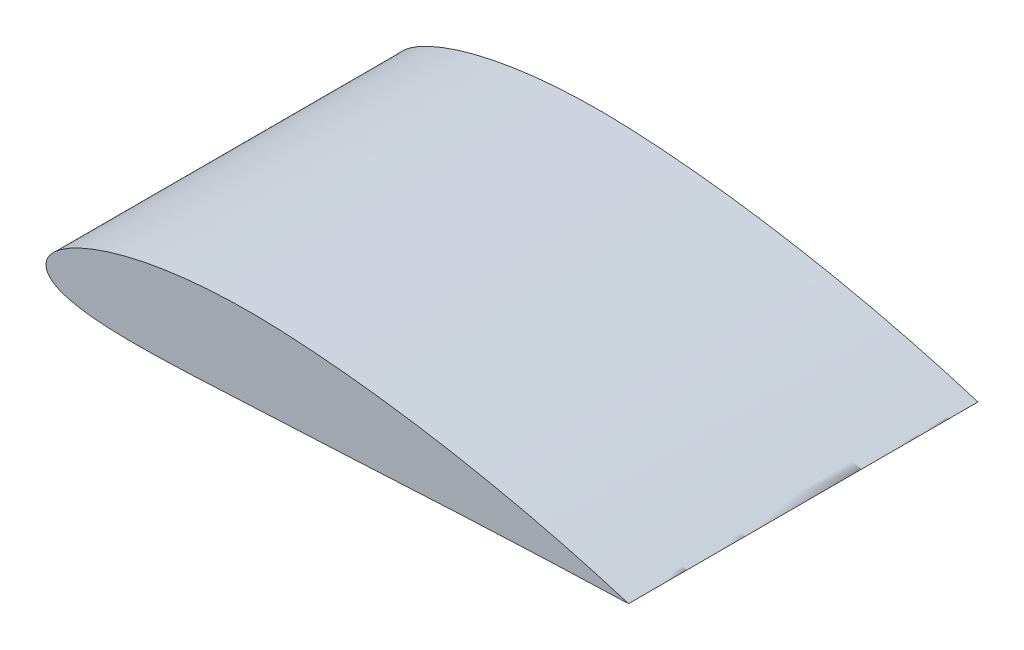
SolidWorks part; units mm, degrees
ref_plane "Front Plane" through (0, 0, 0) normal (1, 0, 0) x (0, 1, 0)
ref_plane "Top Plane" through (0, 0, 0) normal (0, 0, 1) x (0, 1, 0)
ref_plane "Right Plane" through (0, 0, 0) normal (0, 1, 0) x (-1, 0, 0)
curve "Curve1"
  spline degree 3 poles (0.9995, 0, 0) (1.0001, 0, 0) (0.9995, 0.0001, 0) (0.999, 0.0003, 0) (0.9976, 0.0007, 0) (0.996, 0.0012, 0) (0.9938, 0.0019, 0) (0.9912, 0.0027, 0) (0.9881, 0.0036, 0) (0.9845, 0.0047, 0) (0.9804, 0.0059, 0) (0.9759, 0.0073, 0) (0.9709, 0.0088, 0) (0.9655, 0.0104, 0) (0.9596, 0.0121, 0) (0.9532, 0.0139, 0) (0.9464, 0.0158, 0) (0.9392, 0.0179, 0) (0.9316, 0.02, 0) (0.9235, 0.0222, 0) (0.915, 0.0245, 0) (0.9061, 0.0269, 0) (0.8968, 0.0294, 0) (0.8871, 0.0319, 0) (0.877, 0.0345, 0) (0.8665, 0.0371, 0) (0.8557, 0.0397, 0) (0.8445, 0.0424, 0) (0.833, 0.0452, 0) (0.8212, 0.0479, 0) (0.809, 0.0507, 0) (0.7965, 0.0535, 0) (0.7837, 0.0563, 0) (0.7706, 0.059, 0) (0.7573, 0.0618, 0) (0.7436, 0.0645, 0) (0.7298, 0.0673, 0) (0.7157, 0.0699, 0) (0.7013, 0.0726, 0) (0.6868, 0.0752, 0) (0.6721, 0.0777, 0) (0.6571, 0.0802, 0) (0.6421, 0.0826, 0) (0.6268, 0.085, 0) (0.6115, 0.0873, 0) (0.596, 0.0895, 0) (0.5804, 0.0916, 0) (0.5647, 0.0936, 0) (0.5489, 0.0955, 0) (0.5331, 0.0973, 0) (0.5173, 0.099, 0) (0.5014, 0.1006, 0) (0.4855, 0.102, 0) (0.4696, 0.1034, 0) (0.4537, 0.1046, 0) (0.4379, 0.1057, 0) (0.4221, 0.1066, 0) (0.4064, 0.1074, 0) (0.3906, 0.1081, 0) (0.3749, 0.1085, 0) (0.3592, 0.1087, 0) (0.3437, 0.1087, 0) (0.3283, 0.1086, 0) (0.3131, 0.1081, 0) (0.298, 0.1075, 0) (0.2832, 0.1067, 0) (0.2687, 0.1057, 0) (0.2543, 0.1045, 0) (0.2402, 0.103, 0) (0.2264, 0.1014, 0) (0.2129, 0.0996, 0) (0.1997, 0.0977, 0) (0.1868, 0.0955, 0) (0.1743, 0.0932, 0) (0.1621, 0.0908, 0) (0.1502, 0.0882, 0) (0.1388, 0.0854, 0) (0.1277, 0.0826, 0) (0.117, 0.0796, 0) (0.1068, 0.0765, 0) (0.0969, 0.0733, 0) (0.0875, 0.07, 0) (0.0786, 0.0667, 0) (0.07, 0.0632, 0) (0.062, 0.0597, 0) (0.0544, 0.0562, 0) (0.0473, 0.0526, 0) (0.0406, 0.049, 0) (0.0345, 0.0454, 0) (0.0288, 0.0418, 0) (0.0236, 0.0382, 0) (0.019, 0.0346, 0) (0.0148, 0.031, 0) (0.0111, 0.0274, 0) (0.0079, 0.0238, 0) (0.0053, 0.0203, 0) (0.0031, 0.0168, 0) (0.0014, 0.0133, 0) (0.0003, 0.0099, 0) (-0.0004, 0.0066, 0) (-0.0005, 0.0032, 0) (-0.0001, 0, 0) (0.0008, -0.0032, 0) (0.0022, -0.0062, 0) (0.0041, -0.0091, 0) (0.0064, -0.0118, 0) (0.0092, -0.0143, 0) (0.0125, -0.0168, 0) (0.0162, -0.019, 0) (0.0204, -0.0212, 0) (0.0251, -0.0232, 0) (0.0301, -0.025, 0) (0.0357, -0.0267, 0) (0.0416, -0.0283, 0) (0.048, -0.0298, 0) (0.0548, -0.0311, 0) (0.0619, -0.0323, 0) (0.0695, -0.0333, 0) (0.0775, -0.0343, 0) (0.0859, -0.0351, 0) (0.0946, -0.0358, 0) (0.1037, -0.0363, 0) (0.1131, -0.0368, 0) (0.1229, -0.0371, 0) (0.1331, -0.0374, 0) (0.1436, -0.0375, 0) (0.1543, -0.0375, 0) (0.1654, -0.0375, 0) (0.1768, -0.0373, 0) (0.1885, -0.0371, 0) (0.2005, -0.0368, 0) (0.2127, -0.0364, 0) (0.2252, -0.036, 0) (0.2379, -0.0355, 0) (0.2509, -0.0349, 0) (0.2641, -0.0343, 0) (0.2775, -0.0337, 0) (0.2911, -0.033, 0) (0.3049, -0.0324, 0) (0.3189, -0.0316, 0) (0.3331, -0.0309, 0) (0.3474, -0.0302, 0) (0.3619, -0.0295, 0) (0.3765, -0.0288, 0) (0.3913, -0.0281, 0) (0.4063, -0.0274, 0) (0.4215, -0.0267, 0) (0.4368, -0.0259, 0) (0.4522, -0.0252, 0) (0.4676, -0.0244, 0) (0.4831, -0.0236, 0) (0.4986, -0.0228, 0) (0.5141, -0.0219, 0) (0.5297, -0.0211, 0) (0.5452, -0.0203, 0) (0.5606, -0.0194, 0) (0.576, -0.0186, 0) (0.5914, -0.0178, 0) (0.6066, -0.017, 0) (0.6218, -0.0162, 0) (0.6368, -0.0154, 0) (0.6518, -0.0146, 0) (0.6666, -0.0138, 0) (0.6812, -0.0131, 0) (0.6957, -0.0124, 0) (0.71, -0.0117, 0) (0.7241, -0.011, 0) (0.738, -0.0103, 0) (0.7516, -0.0097, 0) (0.765, -0.0091, 0) (0.7782, -0.0085, 0) (0.7911, -0.0079, 0) (0.8037, -0.0074, 0) (0.8161, -0.0069, 0) (0.8281, -0.0064, 0) (0.8398, -0.0059, 0) (0.8512, -0.0054, 0) (0.8622, -0.005, 0) (0.8729, -0.0046, 0) (0.8832, -0.0042, 0) (0.8931, -0.0038, 0) (0.9027, -0.0034, 0) (0.9118, -0.0031, 0) (0.9206, -0.0028, 0) (0.9289, -0.0025, 0) (0.9368, -0.0022, 0) (0.9443, -0.0019, 0) (0.9513, -0.0017, 0) (0.9579, -0.0014, 0) (0.964, -0.0012, 0) (0.9697, -0.001, 0) (0.9749, -0.0009, 0) (0.9796, -0.0007, 0) (0.9838, -0.0006, 0) (0.9875, -0.0004, 0) (0.9908, -0.0003, 0) (0.9935, -0.0002, 0) (0.9958, -0.0001, 0) (0.9975, -0.0001, 0) (0.9989, 0, 0) (0.9995, 0, 0) (1.0001, 0, 0) (0.9995, 0.0001, 0) knots -0.001102 -0.00049 -0.000122 0 0.000122 0.00049 0.001103 0.001958 0.003058 0.004399 0.005981 0.007802 0.00986 0.012153 0.014678 0.017434 0.020418 0.023625 0.027053 0.030699 0.034559 0.038629 0.042904 0.047381 0.052056 0.056923 0.061977 0.067214 0.072628 0.078214 0.083966 0.089879 0.095947 0.102163 0.108523 0.115018 0.121644 0.128392 0.135258 0.142233 0.149312 0.156486 0.163749 0.171095 0.178514 0.186001 0.193548 0.201147 0.208791 0.216472 0.224183 0.231916 0.239663 0.247417 0.25517 0.262915 0.270644 0.278349 0.286022 0.293657 0.301328 0.309003 0.316618 0.324165 0.331637 0.339027 0.346327 0.353532 0.360632 0.367623 0.374498 0.38125 0.387872 0.394359 0.400704 0.406902 0.412948 0.418835 0.424559 0.430114 0.435496 0.440701 0.445724 0.450562 0.455211 0.459668 0.46393 0.467994 0.47186 0.475526 0.478991 0.482256 0.485323 0.488192 0.490869 0.493358 0.495668 0.497809 0.499795 0.501644 0.503379 0.505028 0.506623 0.508203 0.509782 0.511377 0.513024 0.514755 0.516595 0.518566 0.520685 0.522963 0.525411 0.528034 0.530836 0.533822 0.536991 0.540344 0.543881 0.547601 0.551501 0.55558 0.559835 0.564263 0.56886 0.573624 0.57855 0.583634 0.588873 0.594261 0.599795 0.605469 0.61128 0.617223 0.623292 0.629482 0.635788 0.642206 0.64873 0.655353 0.662072 0.668881 0.675773 0.682743 0.689785 0.696894 0.704063 0.711344 0.718755 0.726207 0.733692 0.741203 0.748734 0.756277 0.763824 0.77137 0.778906 0.786425 0.79392 0.801383 0.808808 0.816186 0.823511 0.830776 0.837973 0.845095 0.852135 0.859086 0.865941 0.872693 0.879335 0.885861 0.892263 0.898536 0.904673 0.910666 0.916512 0.922203 0.927733 0.933096 0.938288 0.943301 0.948132 0.952774 0.957224 0.961476 0.965525 0.969367 0.972998 0.976415 0.979612 0.982587 0.985337 0.987858 0.990147 0.992203 0.994022 0.995602 0.996943 0.998042 0.998898 0.99951 0.999878 1 1.000122 1.00049 1.001103 periodic
sketch "Sketch1" plane through (0, 0, 0) normal (0, 0, 1) x (0, 1, 0)
  spline S1 degree 3 poles (0.0001, -149.9192) (-0.0026, -150.0198) (0.0208, -149.922) (0.0505, -149.8425) (0.1083, -149.6453) (0.1849, -149.3999) (0.2844, -149.0724) (0.4053, -148.6773) (0.5469, -148.2095) (0.7095, -147.6714) (0.8922, -147.0626) (1.0942, -146.384) (1.3154, -145.6361) (1.5551, -144.8196) (1.8122, -143.9351) (2.0862, -142.9833) (2.3761, -141.9652) (2.6815, -140.8815) (3.0011, -139.7333) (3.3344, -138.5216) (3.6797, -137.2473) (4.0373, -135.9118) (4.4047, -134.5159) (4.7823, -133.0613) (5.168, -131.549) (5.5615, -129.9805) (5.9614, -128.3573) (6.3669, -126.6807) (6.7767, -124.9523) (7.1898, -123.1737) (7.6053, -121.3467) (8.022, -119.4728) (8.4391, -117.5539) (8.8552, -115.5918) (9.2693, -113.5883) (9.6809, -111.5454) (10.0882, -109.4648) (10.4909, -107.3488) (10.8877, -105.1994) (11.2773, -103.0185) (11.6596, -100.8084) (12.0325, -98.5711) (12.3961, -96.309) (12.7489, -94.0241) (13.0903, -91.7189) (13.4189, -89.3954) (13.7347, -87.0563) (14.0362, -84.7036) (14.3226, -82.3398) (14.5933, -79.9673) (14.8478, -77.5886) (15.0846, -75.2059) (15.3041, -72.8218) (15.5046, -70.4387) (15.6859, -68.059) (15.8478, -65.6853) (15.989, -63.32) (16.1102, -60.957) (16.2095, -58.5928) (16.2752, -56.2293) (16.31, -53.8781) (16.3124, -51.5475) (16.2833, -49.2403) (16.2222, -46.9592) (16.1298, -44.7066) (16.0067, -42.4854) (15.8525, -40.2979) (15.669, -38.1469) (15.456, -36.0346) (15.2147, -33.9637) (14.9456, -31.9364) (14.6504, -29.9551) (14.3293, -28.022) (13.9841, -26.1393) (13.6156, -24.3091) (13.2253, -22.5334) (12.8143, -20.8142) (12.3844, -19.1533) (11.9364, -17.5525) (11.4724, -16.0135) (10.9934, -14.538) (10.5014, -13.1272) (9.9976, -11.7827) (9.4838, -10.5056) (8.9609, -9.2976) (8.4315, -8.1591) (7.8959, -7.0917) (7.3564, -6.0959) (6.814, -5.1728) (6.2705, -4.3228) (5.7265, -3.5468) (5.1837, -2.8451) (4.643, -2.2183) (4.1055, -1.6664) (3.5718, -1.1902) (3.043, -0.7893) (2.5194, -0.4643) (2.0014, -0.2153) (1.4893, -0.0429) (0.9839, 0.0531) (0.4855, 0.0712) (-0.0024, 0.0124) (-0.4755, -0.1209) (-0.9285, -0.3288) (-1.3589, -0.6093) (-1.7666, -0.9613) (-2.1516, -1.3841) (-2.515, -1.8759) (-2.8563, -2.4367) (-3.1768, -3.065) (-3.4758, -3.7606) (-3.7541, -4.5223) (-4.0119, -5.3494) (-4.2491, -6.241) (-4.4665, -7.1957) (-4.6637, -8.2127) (-4.8414, -9.2907) (-4.9997, -10.4286) (-5.1394, -11.6251) (-5.2601, -12.8792) (-5.3632, -14.1892) (-5.4482, -15.554) (-5.5163, -16.9721) (-5.5678, -18.4423) (-5.6032, -19.9631) (-5.6235, -21.5331) (-5.6287, -23.1508) (-5.6204, -24.8148) (-5.5988, -26.5235) (-5.5647, -28.2756) (-5.5195, -30.0695) (-5.4632, -31.9037) (-5.3973, -33.7766) (-5.3227, -35.6868) (-5.2403, -37.6326) (-5.1511, -39.6124) (-5.0559, -41.6247) (-4.9563, -43.6678) (-4.8525, -45.74) (-4.7463, -47.8398) (-4.6381, -49.9654) (-4.5294, -52.1151) (-4.4209, -54.2871) (-4.314, -56.4797) (-4.2085, -58.697) (-4.1077, -60.9457) (-4.0022, -63.2232) (-3.8914, -65.5216) (-3.7768, -67.8302) (-3.6588, -70.1467) (-3.5381, -72.469) (-3.4154, -74.795) (-3.2912, -77.1224) (-3.1661, -79.4491) (-3.0404, -81.7727) (-2.9152, -84.0911) (-2.7904, -86.4021) (-2.6664, -88.7035) (-2.5441, -90.9929) (-2.4233, -93.2681) (-2.3047, -95.527) (-2.1885, -97.7672) (-2.0746, -99.9867) (-1.9637, -102.1831) (-1.8555, -104.3543) (-1.7505, -106.4981) (-1.6487, -108.6124) (-1.55, -110.695) (-1.4548, -112.7439) (-1.3631, -114.7568) (-1.2746, -116.7318) (-1.1894, -118.6669) (-1.1077, -120.5601) (-1.0293, -122.4094) (-0.9541, -124.2128) (-0.8823, -125.9686) (-0.8137, -127.6748) (-0.7479, -129.3296) (-0.6857, -130.9314) (-0.626, -132.4784) (-0.5696, -133.969) (-0.5158, -135.4015) (-0.4652, -136.7745) (-0.4172, -138.0865) (-0.372, -139.336) (-0.3294, -140.5217) (-0.2895, -141.6422) (-0.2521, -142.6964) (-0.2175, -143.6831) (-0.1857, -144.6013) (-0.156, -145.4497) (-0.1293, -146.2277) (-0.1047, -146.9342) (-0.083, -147.5685) (-0.0639, -148.1298) (-0.047, -148.6179) (-0.0329, -149.0306) (-0.0216, -149.3726) (-0.0118, -149.6294) (-0.0073, -149.8348) (0.0001, -149.9192) (-0.0026, -150.0198) (0.0208, -149.922) knots -0.001102 -0.00049 -0.000122 0 0.000122 0.00049 0.001103 0.001958 0.003058 0.004399 0.005981 0.007802 0.00986 0.012153 0.014678 0.017434 0.020418 0.023625 0.027053 0.030699 0.034559 0.038629 0.042904 0.047381 0.052056 0.056923 0.061977 0.067214 0.072628 0.078214 0.083966 0.089879 0.095947 0.102163 0.108523 0.115018 0.121644 0.128392 0.135258 0.142233 0.149312 0.156486 0.163749 0.171095 0.178514 0.186001 0.193548 0.201147 0.208791 0.216472 0.224183 0.231916 0.239663 0.247417 0.25517 0.262915 0.270644 0.278349 0.286022 0.293657 0.301328 0.309003 0.316618 0.324165 0.331637 0.339027 0.346327 0.353532 0.360632 0.367623 0.374498 0.38125 0.387872 0.394359 0.400704 0.406902 0.412948 0.418835 0.424559 0.430114 0.435496 0.440701 0.445724 0.450562 0.455211 0.459668 0.46393 0.467994 0.47186 0.475526 0.478991 0.482256 0.485323 0.488192 0.490869 0.493358 0.495668 0.497809 0.499795 0.501644 0.503379 0.505028 0.506623 0.508203 0.509782 0.511377 0.513024 0.514755 0.516595 0.518566 0.520685 0.522963 0.525411 0.528034 0.530836 0.533822 0.536991 0.540344 0.543881 0.547601 0.551501 0.55558 0.559835 0.564263 0.56886 0.573624 0.57855 0.583634 0.588873 0.594261 0.599795 0.605469 0.61128 0.617223 0.623292 0.629482 0.635788 0.642206 0.64873 0.655353 0.662072 0.668881 0.675773 0.682743 0.689785 0.696894 0.704063 0.711344 0.718755 0.726207 0.733692 0.741203 0.748734 0.756277 0.763824 0.77137 0.778906 0.786425 0.79392 0.801383 0.808808 0.816186 0.823511 0.830776 0.837973 0.845095 0.852135 0.859086 0.865941 0.872693 0.879335 0.885861 0.892263 0.898536 0.904673 0.910666 0.916512 0.922203 0.927733 0.933096 0.938288 0.943301 0.948132 0.952774 0.957224 0.961476 0.965525 0.969367 0.972998 0.976415 0.979612 0.982587 0.985337 0.987858 0.990147 0.992203 0.994022 0.995602 0.996943 0.998042 0.998898 0.99951 0.999878 1 1.000122 1.00049 1.001103 only from (0, -150) to (0, -150)
extrude "Boss-Extrude1" add sketch "Sketch1" along normal blind 90
